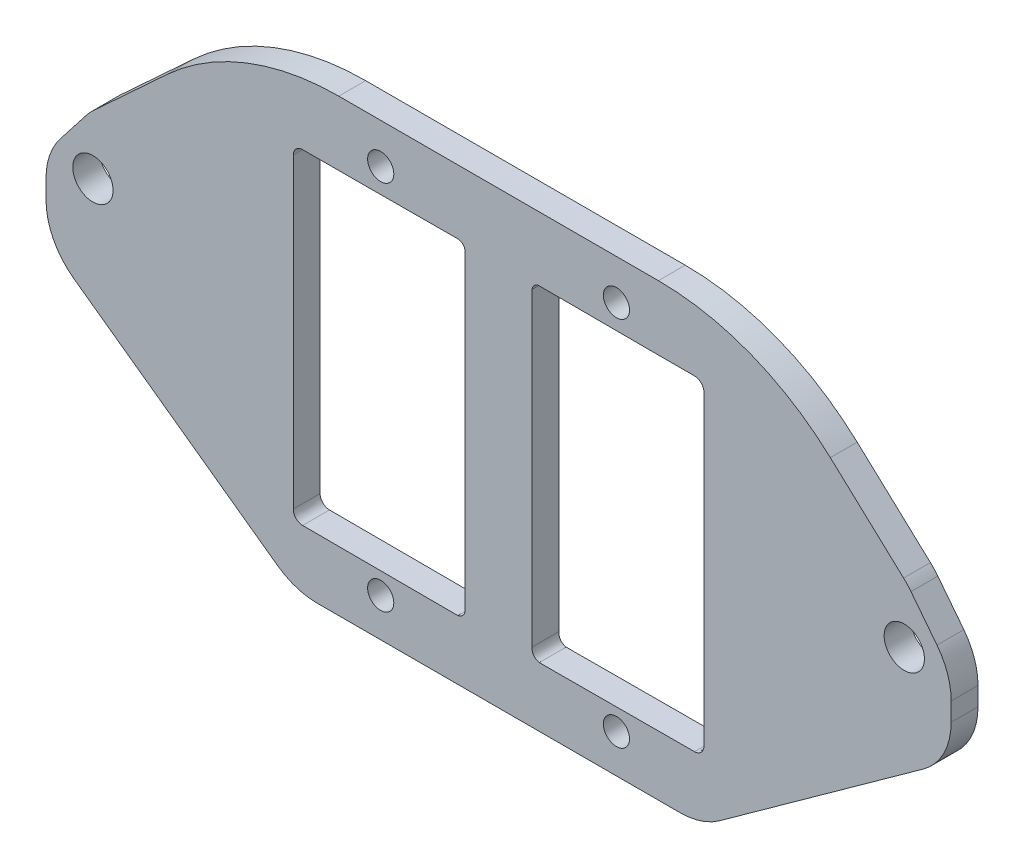
SolidWorks part; units mm, degrees
material "ABS"
ref_plane "Plan de face" through (0, 0, 0) normal (0, 0, 1) x (1, 0, 0)
ref_plane "Plan de dessus" through (0, 0, 0) normal (0, 1, 0) x (1, 0, 0)
ref_plane "Plan de droite" through (0, 0, 0) normal (1, 0, 0) x (0, 0, -1)
sketch "Esquisse1" plane through (0, 0, 0) normal (0, 0, 1) x (1, 0, 0)
  line B0 (31.6406, -4.8872) -> (16.4505, -15.8195)
  line B1 (-24.7195, 11.748) -> (-30.1767, 6.7065)
  line B2 (-2.5, 11.4872) -> (-2.5, -11.5766)
  line B3 (-11.1283, 11.9611) -> (-3.0874, 11.9879)
  line B4 (-14.5979, 11.9611) -> (-11.1283, 11.9611)
  line B5 (-15.2981, -11.5761) -> (-15.298, 11.2611)
  line B6 (-3.0331, -12.3196) -> (-14.5979, -12.2853)
  line B7 (-30.7275, 6.1076) -> (-32.6635, 3.6237)
  line B8 (-33.7198, 0.55) -> (-33.7198, -0.829)
  line B9 (-31.6406, -4.8872) -> (-16.4505, -15.8195)
  line B10 (33.7198, 0.55) -> (33.7198, -0.829)
  line B11 (30.7275, 6.1076) -> (32.6635, 3.6237)
  line B12 (3.0331, -12.3196) -> (14.5979, -12.2853)
  line B13 (15.2981, -11.5761) -> (15.298, 11.2611)
  line B14 (14.5979, 11.9611) -> (11.1283, 11.9611)
  line B15 (11.1283, 11.9611) -> (3.0874, 11.9879)
  line B16 (2.5, 11.4872) -> (2.5, -11.5766)
  line B17 (24.7195, 11.748) -> (30.1767, 6.7065)
  line B18 (0, 16.7612) -> (0, -16.7612) construction
  line B19 (-11.905, 16.7612) -> (11.905, 16.7612)
  line B20 (13.5298, -16.7612) -> (-13.5298, -16.7612)
  arc B21 (-16.4505, -15.8195) -> (-13.5298, -16.7612) centre (-13.5298, -11.7612) ccw
  arc B22 (-33.7198, -0.829) -> (-31.6406, -4.8872) centre (-28.7198, -0.829) ccw
  circle B23 centre (-30.2257, 2.2684) radius 1.5
  arc B24 (-32.6635, 3.6237) -> (-33.7198, 0.55) centre (-28.7198, 0.55) ccw
  circle B25 centre (-8.7821, 13.7811) radius 0.975
  circle B26 centre (-8.7821, -13.8889) radius 0.975
  arc B27 (-30.1767, 6.7065) -> (-30.7275, 6.1076) centre (-26.7839, 3.0338) ccw
  arc B28 (-11.905, 16.7612) -> (-24.7195, 11.748) centre (-11.905, -2.1232) ccw
  arc B29 (11.905, 16.7612) -> (24.7195, 11.748) centre (11.905, -2.1232) cw
  arc B30 (30.1767, 6.7065) -> (30.7275, 6.1076) centre (26.7839, 3.0338) cw
  circle B31 centre (8.7821, -13.8889) radius 0.975
  circle B32 centre (8.7821, 13.7811) radius 0.975
  arc B33 (32.6635, 3.6237) -> (33.7198, 0.55) centre (28.7198, 0.55) cw
  circle B34 centre (30.2257, 2.2684) radius 1.5
  arc B35 (33.7198, -0.829) -> (31.6406, -4.8872) centre (28.7198, -0.829) cw
  arc B36 (16.4505, -15.8195) -> (13.5298, -16.7612) centre (13.5298, -11.7612) cw
  spline B37 degree 3 poles (-2.5, -11.5766) (-2.4732, -11.7394) (-2.5536, -12.101) (-2.8703, -12.2928) (-3.0331, -12.3196) knots 0 0 0 0 0.785398 1.570796 1.570796 1.570796 1.570796
  spline B38 degree 3 poles (-3.0874, 11.9879) (-2.9486, 11.9989) (-2.6502, 11.9059) (-2.5111, 11.626) (-2.5, 11.4872) knots 1.570796 1.570796 1.570796 1.570796 2.356194 3.141593 3.141593 3.141593 3.141593
  spline B39 degree 3 poles (14.5979, -12.2853) (14.7777, -12.2841) (15.1512, -12.1314) (15.2992, -11.7558) (15.2981, -11.5761) knots 1.570796 1.570796 1.570796 1.570796 2.356194 3.141593 3.141593 3.141593 3.141593
  spline B40 degree 3 poles (15.298, 11.2611) (15.298, 11.4397) (15.1486, 11.8119) (14.7765, 11.9611) (14.5979, 11.9611) knots 0 0 0 0 0.785398 1.570796 1.570796 1.570796 1.570796
  spline B41 degree 3 poles (-15.298, 11.2611) (-15.298, 11.4397) (-15.1486, 11.8119) (-14.7765, 11.9611) (-14.5979, 11.9611) knots 0 0 0 0 0.785398 1.570796 1.570796 1.570796 1.570796
  spline B42 degree 3 poles (-14.5979, -12.2853) (-14.7777, -12.2841) (-15.1512, -12.1314) (-15.2992, -11.7558) (-15.2981, -11.5761) knots 1.570796 1.570796 1.570796 1.570796 2.356194 3.141593 3.141593 3.141593 3.141593
  spline B43 degree 3 poles (3.0874, 11.9879) (2.9486, 11.9989) (2.6502, 11.9059) (2.5111, 11.626) (2.5, 11.4872) knots 1.570796 1.570796 1.570796 1.570796 2.356194 3.141593 3.141593 3.141593 3.141593
  spline B44 degree 3 poles (2.5, -11.5766) (2.4732, -11.7394) (2.5536, -12.101) (2.8703, -12.2928) (3.0331, -12.3196) knots 0 0 0 0 0.785398 1.570796 1.570796 1.570796 1.570796
sketch_block_instance "Bloc5-1"
sketch_block "Bloc5" parameters "D2"=5, "D3"=5, "D1"=2.5
extrude "Boss.-Extru.3" add sketch "Esquisse1" along normal blind 2
sketch "Esquisse2" plane through (0, 0, 2) normal (0, 0, 1) x (1, 0, 0)
  circle A0 centre (29.9555, 19.7622) radius 1.5
  circle A1 centre (-60.2396, 19.7622) radius 1.5
extrude "Enlèv. mat.-Extru.1" cut sketch "Esquisse2" against normal blind 10
